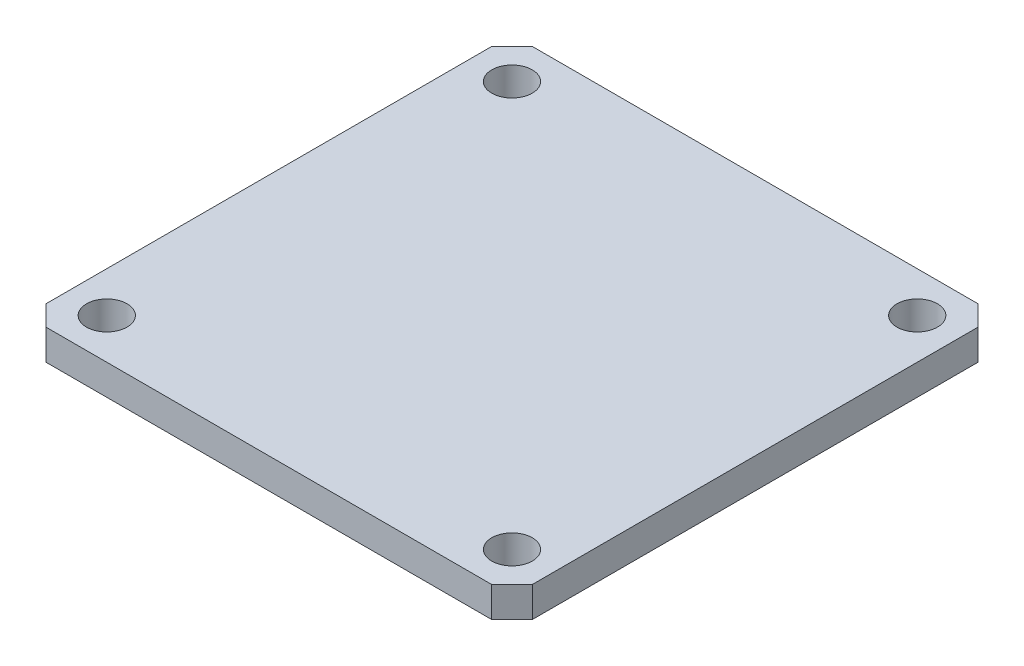
SolidWorks part; units mm, degrees
ref_plane "Front Plane" through (0, 0, 0) normal (0, 0, 1) x (1, 0, 0)
ref_plane "Top Plane" through (0, 0, 0) normal (0, 1, 0) x (1, 0, 0)
ref_plane "Right Plane" through (0, 0, 0) normal (1, 0, 0) x (0, 0, -1)
sketch "Sketch1" plane through (0, 0, 0) normal (0, 1, 0) x (1, 0, 0)
  line L1 (12, -12) -> (-12, -12)
  line L2 (12, -12) -> (12, 12)
  line L3 (12, 12) -> (-12, 12)
  line L4 (-12, -12) -> (-12, 12)
  line L5 (12, -12) -> (-12, 12) construction
  line L6 (12, 12) -> (-12, -12) construction
  point P0 (0, 0)
  dimension "D1" = 24
  dimension "D2" = 24
extrude "Boss-Extrude1" add sketch "Sketch1" along normal blind 1.5
chamfer "Chamfer1" distance 1 angle 45 4 edges at (-12, 0.75, -12) (12, 0.75, -12) (-12, 0.75, 12) (12, 0.75, 12)
sketch "Sketch2" plane through (0, 1.5, 0) normal (0, 1, 0) x (1, 0, 0)
  line L1 (10, -10) -> (-10, -10) construction
  line L2 (10, -10) -> (10, 10) construction
  line L3 (10, 10) -> (-10, 10) construction
  line L4 (-10, -10) -> (-10, 10) construction
  line L5 (10, -10) -> (-10, 10) construction
  line L6 (10, 10) -> (-10, -10) construction
  circle A0 centre (-10, 10) radius 1
  circle A1 centre (10, 10) radius 1
  circle A2 centre (10, -10) radius 1
  circle A3 centre (-10, -10) radius 1
  point P0 (0, 0)
  dimension "D3" = 2
  dimension "D1" = 20
  dimension "D2" = 20
extrude "Cut-Extrude1" cut sketch "Sketch2" against normal up to surface (1.5 mm away) up to face at (0, 0, 0)
